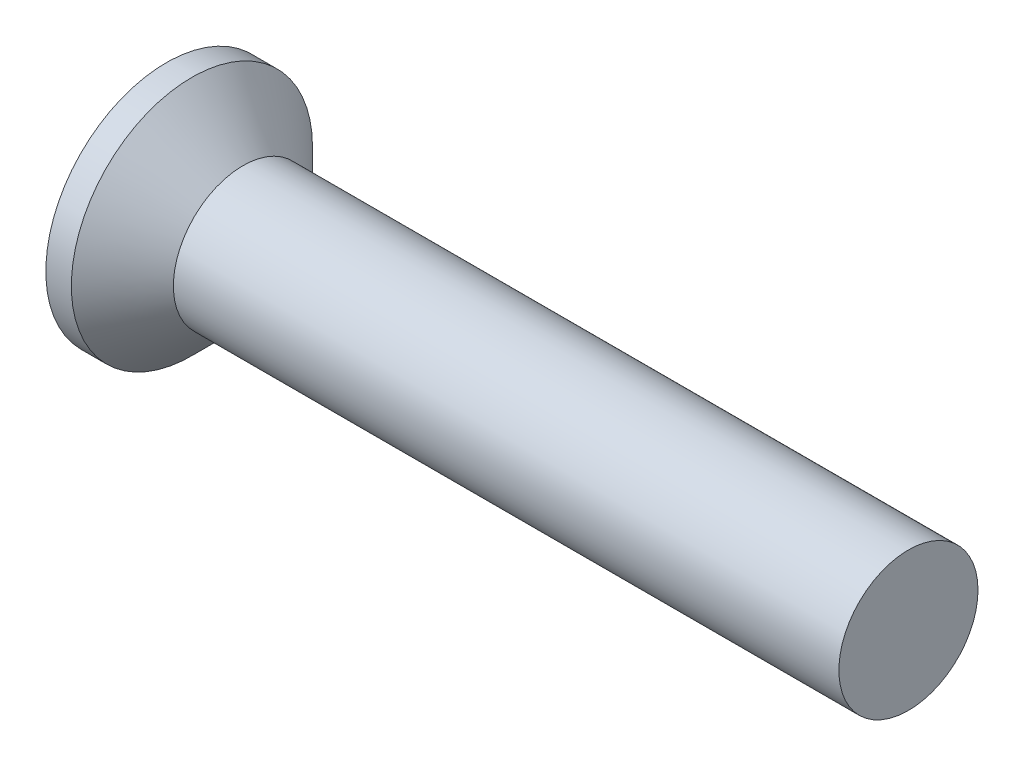
SolidWorks part; units mm, degrees
ref_plane "Front" through (0, 0, 0) normal (0, 0, 1) x (1, 0, 0)
ref_plane "Top" through (0, 0, 0) normal (0, 1, 0) x (1, 0, 0)
ref_plane "Right" through (0, 0, 0) normal (1, 0, 0) x (0, 0, -1)
other "Configuration Table"
sketch "Sketch1" plane through (0, 0, 0) normal (0, 0, 1) x (1, 0, 0)
  line L0 (16, 1.5) -> (2.65, 1.5)
  line L1 (2.65, 1.5) -> (1.65, 1.5)
  line L2 (1.65, 1.5) -> (0.55, 2.6)
  line L3 (0.55, 2.6) -> (0, 2.6)
  line L4 (16, 1.5) -> (16, 0)
  line L5 (4.5158, 0) -> (-89.8219, 0) construction
  line L6 (16, 0) -> (0, 0)
  line L7 (0, 2.6) -> (0, 0)
  dimension "d" = 3
  dimension "D1" = 45
  dimension "dk" = 5.2
  dimension "k" = 1.65
  dimension "l" = 16
  dimension "a" = 1
revolve "Base" add sketch "Sketch1" angle 360 about L5
cosmetic thread "ThreadCosmetic1" [suppressed] parameters "bb"=14.35, "THD_MINOR"=2.459
sketch "Sketch6" plane through (0, 0, 0) normal (1, 0, 0) x (0, 0, -1)
  line L0 (-1.9271, 0) -> (2.0512, 0) construction
  line L1 (0, 1.8651) -> (0, -2.0207) construction
  line L2 (0.32, 0.32) -> (0.32, 1.6)
  line L3 (0.32, 1.6) -> (-0.32, 1.6)
  line L4 (-0.32, 0.32) -> (-0.32, 1.6)
  line L5 (0.32, 0.32) -> (1.6, 0.32)
  line L6 (1.6, 0.32) -> (1.6, -0.32)
  line L7 (-1.6, 0.32) -> (-1.6, -0.32)
  line L8 (-0.32, 0.32) -> (-1.6, 0.32)
  line L9 (-0.32, -0.32) -> (-1.6, -0.32)
  line L10 (0.32, -0.32) -> (1.6, -0.32)
  line L11 (-0.32, -0.32) -> (-0.32, -1.6)
  line L12 (0.32, -1.6) -> (-0.32, -1.6)
  line L13 (0.32, -0.32) -> (0.32, -1.6)
  point P16 (-1.6, 0)
  point P17 (1.6, 0)
extrude "CrossRecess" cut sketch "Sketch6" along normal blind 0.825
draft "Draft9" type of draft neutral plane draft angle 30 faces to draft 4 face at (0.4125, 1.6, 0) face at (0.4125, 0, 1.6) face at (0.4125, -1.6, 0) face at (0.4125, 0, -1.6) neutral plane through (0, 2.6, 0) neutral plane normal (-1, 0, 0) parameters "D1"=30
fillet "Fillet5" radius 0.3 4 edges at (0.4125, -0.32, -0.32) (0.4125, 0.32, -0.32) (0.4125, 0.32, 0.32) (0.4125, -0.32, 0.32)
sketch "Sketch7" plane through (0, 0, 0) normal (1, 0, 0) x (0, 0, -1)
  line L0 (-2.0126, 0) -> (1.9757, 0) construction
  line L1 (0, 1.9314) -> (0, -2.0126) construction
  line L2 (0, 0) -> (1.5555, 1.5555) construction
  line L3 (0, 0.4782) -> (1.1314, 1.1314)
  line L4 (-1.5402, 1.5402) -> (0, 0) construction
  line L5 (0.4782, 0) -> (1.1314, 1.1314)
  line L6 (0, -0.4782) -> (1.1314, -1.1314)
  line L7 (0.4782, 0) -> (1.1314, -1.1314)
  line L8 (-0.4782, 0) -> (-1.1314, -1.1314)
  line L9 (0, -0.4782) -> (-1.1314, -1.1314)
  line L10 (-0.4782, 0) -> (-1.1314, 1.1314)
  line L11 (0, 0.4782) -> (-1.1314, 1.1314)
  dimension "D3" = 15
  dimension "m" = 3.2
extrude "Cut-Extrude3" [suppressed] cut sketch "Sketch7" along normal blind 10 draft 20
sketch "Sketch8" plane through (0, 0, 0) normal (0, 0, 1) x (1, 0, 0)
  line L0 (-9, 1.7705) -> (-10.25, 1.5)
  line L1 (-10.25, 1.5) -> (1.65, 1.5)
  line L3 (16, -1.5) -> (16, 1.5) construction
  line L6 (1.65, 1.5) -> (1.65, 6.5)
  line L7 (1.65, 6.5) -> (-9, 6.5)
  line L8 (-9, 6.5) -> (-9, 1.7705)
  line L9 (62.4753, 0.2705) -> (52.9594, 0.2705) construction
  dimension "D1" = 5
  dimension "x" = 1.25
  dimension "d" = 3
  dimension "THD_MINOR" = 2.459
  dimension "b" = 25
sketch "Sketch9" plane through (0, 0, 0) normal (0, 0, 1) x (1, 0, 0)
  line L0 (16, 1.2657) -> (16.1352, 1.5)
  line L1 (16.1352, 1.5) -> (16.1352, 1.7705)
  line L2 (16.1352, 1.7705) -> (15.8648, 1.7705)
  line L3 (15.8648, 1.7705) -> (15.8648, 1.5)
  line L4 (15.8648, 1.5) -> (16, 1.2657)
  line L5 (0, 0) -> (73.843, 0) construction
  line L6 (16, -1.5) -> (16, 1.5) construction
  dimension "D1" = 3
  dimension "D2" = 0.2705
revolve "Cut-Revolve10" [suppressed] cut sketch "Sketch9" angle 360 about L5
pattern_linear "LPattern10" [suppressed] count 44 spacing 0.3246 along (1, 0, 0)
equation "\"D1@Sketch6\" = \"m@Sketch6\" / 5"
equation "\"D1@CrossRecess\" = \"k@Sketch1\" / 2"
equation "\"D1@Sketch9\" = \"d@Sketch1\""
equation "\"D2@Sketch9\" =  ( \"d@Sketch1\" - \"THD_MINOR@ThreadCosmetic1\" )  / 2"
equation "\"D3@LPattern10\" = \"D2@Sketch9\" * 1.2"
equation "\"D1@LPattern10\" = \"bb@ThreadCosmetic1\" / \"D3@LPattern10\" "
